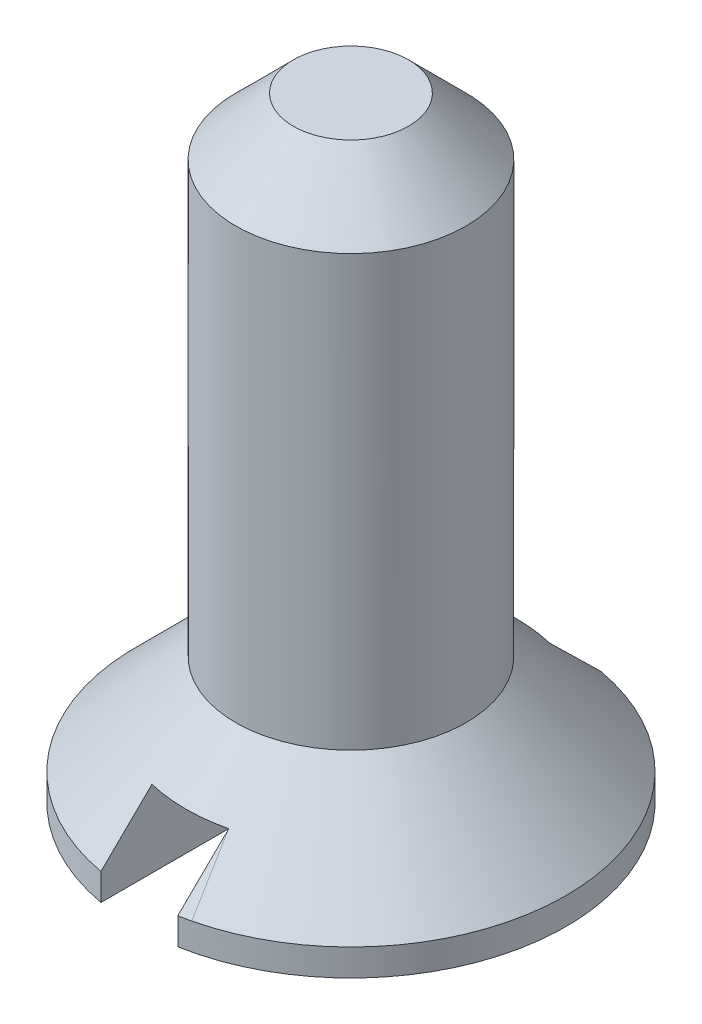
SolidWorks part; units mm, degrees
ref_plane "Спереди" through (0, 0, 0) normal (0, 0, 1) x (1, 0, 0)
ref_plane "Сверху" through (0, 0, 0) normal (0, 1, 0) x (1, 0, 0)
ref_plane "Справа" through (0, 0, 0) normal (1, 0, 0) x (0, 0, -1)
sketch "Эскиз1" plane through (0, 0, 0) normal (0, 0, 1) x (1, 0, 0)
  line L0 (0, 0) -> (-2.8, 0)
  line L1 (-2.8, 0) -> (-2.8, 0.35)
  line L2 (-2.8, 0.35) -> (-1.5, 1.65)
  line L3 (-1.5, 1.65) -> (-1.5, 8)
  line L4 (-1.5, 8) -> (0, 8)
  line L5 (0, 8) -> (0, 0)
  line L6 (-1.5, 1.65) -> (0, 1.65) construction
  line L7 (0, 0) -> (2.8, 0) construction
  dimension "D1" = 8
  dimension "D2" = 5.6
  dimension "D3" = 1.5
  dimension "D4" = 45
  dimension "D5" = 1.65
revolve "Повернуть1" add sketch "Эскиз1" angle 360 about L5
sketch "Эскиз2" plane through (0, 0, 0) normal (0, 0, 1) x (1, 0, 0)
  line L0 (-2.8, 0) -> (2.8, 0) construction
  line L1 (-0.5, 0) -> (0.5, 0)
  line L2 (-0.5, 0) -> (-0.5, 1)
  line L3 (-0.5, 1) -> (0.5, 1)
  line L4 (0.5, 0) -> (0.5, 1)
  dimension "D1" = 1
  dimension "D2" = 1
extrude "Вырез-Вытянуть1" cut sketch "Эскиз2" against normal mid plane 20
chamfer "Фаска1" distance 0.75 angle 45 1 edges at (-1.5, 8, 0)
